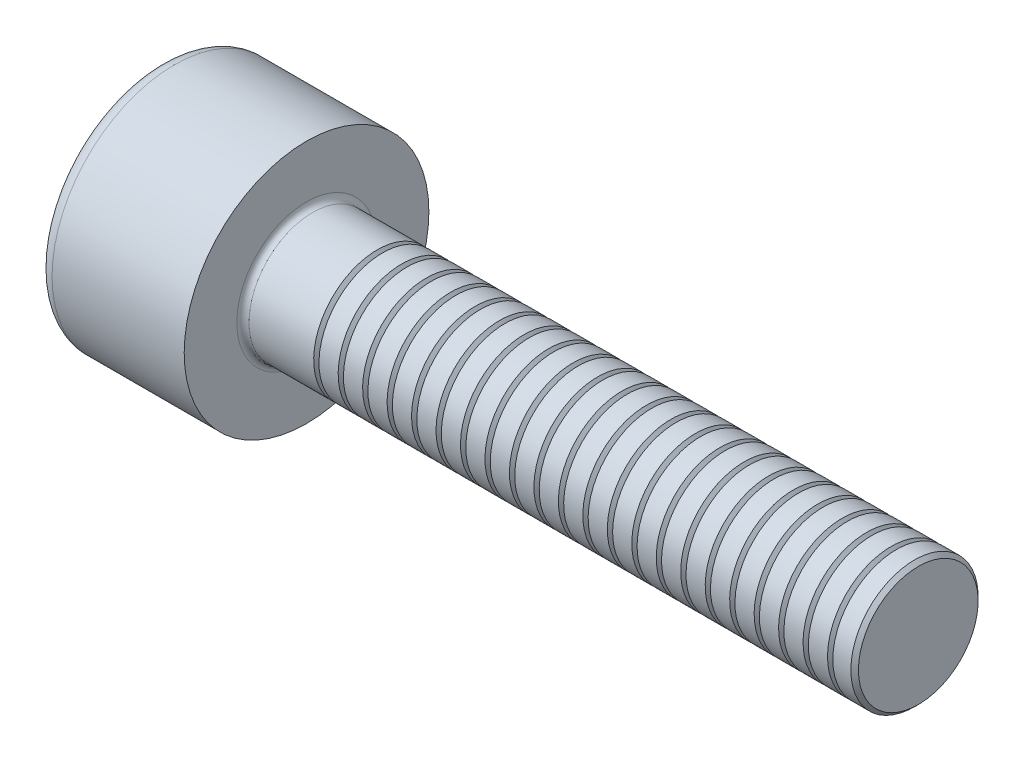
SolidWorks part; units mm, degrees
revolve "Base-Revolve" add sketch "BodySke"
sketch "BodySke" plane through (0, 0, 0) normal (0, 0, 1) x (1, 0, 0)
  line L0 (0, 0) -> (0, 5)
  line L1 (0, 5) -> (6, 5)
  line L2 (6, 5) -> (6, 2.6)
  line L3 (6, 2.6) -> (30.8455, 2.6)
  line L4 (31, 2.4455) -> (31, 0)
  line L5 (31, 0) -> (0, 0)
  line L6 (-31.75, 0) -> (127, 0) construction
  line L8 (31, 2.4455) -> (30.8455, 2.6)
  line L10 (31, -2.4455) -> (30.8455, -2.6) construction
  line L11 (7, 9.525) -> (7, 3.175) construction
  line L12 (6, 9.525) -> (6, 3.175) construction
  line L13 (-29, 9.525) -> (-29, 3.175) construction
  dimension "Head_ht" = 6
  dimension "Length" = 25
  dimension "Body_ch_ang" = 45
  dimension "Diameter" = 5.2
  dimension "Minor_dia" = 4.891
  dimension "Advance" = 1
  dimension "Thread_nom" = 25
  dimension "Thread_length" = 60
  dimension "Head_dia" = 10
cosmetic thread "ThreadCosmetic"
fillet "Fillet1" radius 0.25 1 edges at (6, 0, 2.6)
fillet "Fillet2" radius 0.6 1 edges at (0, 0, 5)
material "Parafusos"
ref_plane "Plane1" through (0, 0, 0) normal (0, 0, 1) x (1, 0, 0)
ref_plane "Plane2" through (0, 0, 0) normal (0, 1, 0) x (1, 0, 0)
ref_plane "Plane3" through (0, 0, 0) normal (1, 0, 0) x (0, 0, -1)
sketch "Sketch2" plane through (0, 0, 0) normal (0, 0, 1) x (1, 0, 0)
  line L0 (0, 2.51) -> (3, 2.51)
  line L1 (3, 2.51) -> (4.4491, 0)
  line L2 (-31.75, 0) -> (127, 0) construction
  line L3 (4.4491, 0) -> (0, 0)
  line L4 (0, 0) -> (0, 2.51)
  line L6 (0, 0) -> (47.625, 0) construction
  dimension "D1" = 2.51
  dimension "D2" = 60
  dimension "Depth" = 3
revolve "Hex-PreBroach" cut sketch "Sketch2" angle 360 about L6
sketch "Sketch3" plane through (0, 0, 0) normal (-1, 0, 0) x (0, 0.5, 0.866)
  line L0 (1.4491, 2.51) -> (-1.4491, 2.51)
  line L1 (-1.4491, 2.51) -> (-2.8983, 0)
  line L2 (1.4491, 2.51) -> (2.8983, 0)
  line L3 (1.4491, -2.51) -> (2.8983, 0)
  line L4 (1.4491, -2.51) -> (-1.4491, -2.51)
  line L5 (-1.4491, -2.51) -> (-2.8983, 0)
  dimension "D1" = 2.51
  dimension "D2" = 2.51
  dimension "Hex_size" = 5.02
extrude "Hex" cut sketch "Sketch3" against normal blind 3
sketch "ThdSchSke" plane through (0, 0, 0) normal (0, 0, 1) x (1, 0, 0)
  line L0 (9, -2.4455) -> (8.8918, -2.6)
  line L1 (9, -2.4455) -> (9.1082, -2.6)
  line L2 (9.1082, -2.6) -> (9.1082, -3.25)
  line L3 (-3.175, 0) -> (5.1513, 0) construction
  line L4 (0, 4.4) -> (0, -4.4) construction
  line L5 (9.1082, -3.25) -> (8.8918, -3.25)
  line L6 (8.8918, -3.25) -> (8.8918, -2.6)
  dimension "Thread_minor" = 4.891
  dimension "Diameter" = 5.2
  dimension "Start" = 9
revolve "ThreadSchematic" cut sketch "ThdSchSke" angle 360 about L3
pattern_linear "ThdSchPat" count 22 spacing 1 along (1, 0, 0) of "ThreadSchematic"
equation "\"D2@Sketch3\" = \"Hex_size@Sketch3\" / 2"
equation "\"D1@Sketch3\" = \"Hex_size@Sketch3\" / 2"
equation "\"D1@Sketch2\" = \"Hex_size@Sketch3\" / 2"
equation "\"Thread_minor@ThreadCosmetic\"  =  \"Minor_dia@BodySke\""
equation "\"Depth@Sketch2\" =  \"Key_eng@Hex\""
equation "\"Thread_length@ThreadCosmetic\" = ((sgn( (\"Length@BodySke\" - \"Advance@BodySke\" * 3.0) - \"Thread_nom@BodySke\" )-1)*( (\"Length@BodySke\" - \"Advance@BodySke\" * 3.0) - \"Thread_nom@BodySke\" ))/-2+ \"Thread_nom@BodySke\""
equation "\"Thread_minor@ThdSchSke\" = \"Minor_dia@BodySke\""
equation "\"Diameter@ThdSchSke\" = \"Diameter@BodySke\""
equation "\"Overcut@ThdSchSke\" = \"Diameter@BodySke\" * 1.25"
equation "\"Start@ThdSchSke\" = \"Head_ht@BodySke\" + \"Length@BodySke\" - \"Thread_length@ThreadCosmetic\"  '---Non-countersunk---"
equation "\"Num_threads@ThdSchPat\" = int( \"Thread_length@ThreadCosmetic\" / \"Advance@BodySke\" + 0.999 )  + 1"
equation "\"Advance@ThdSchPat\" = \"Thread_length@ThreadCosmetic\" /  (\"Num_threads@ThdSchPat\" - 1) 'relax it"
equation "\"Num_threads@ThdSchPat\" = \"Num_threads@ThdSchPat\" - sgn( \"Num_threads@ThdSchPat\" - 1) '---chamfered tips only---"
